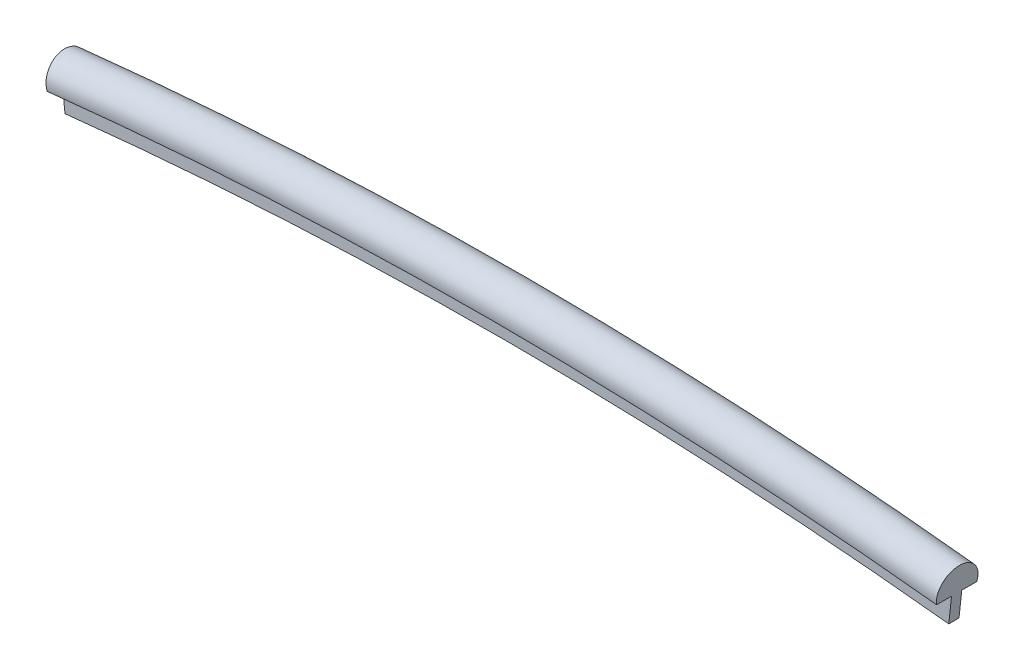
SolidWorks part; units mm, degrees
ref_plane "Front Plane" through (0, 0, 0) normal (0, 0, 1) x (1, 0, 0)
ref_plane "Top Plane" through (0, 0, 0) normal (0, 1, 0) x (1, 0, 0)
ref_plane "Right Plane" through (0, 0, 0) normal (1, 0, 0) x (0, 0, -1)
sketch "Sketch2" plane through (0, 0, 0) normal (1, 0, 0) x (0, 0, -1)
  line L0 (0, 241.3) -> (0, 0) construction
  line L2 (0, 241.3) -> (0, 239.8) construction
  line L3 (0, 239.8) -> (0.3, 239.8)
  line L4 (0, 239.8) -> (-0.3, 239.8)
  line L5 (-0.3, 239.8) -> (-0.3, 241.3)
  line L6 (0.3, 239.8) -> (0.3, 241.3)
  line L7 (0, 241.3) -> (0, 242.8) construction
  line L8 (-1.18, 241.3) -> (-0.3, 241.3)
  line L9 (0.3, 241.3) -> (1.18, 241.3)
  arc A0 (-1.18, 241.3) -> (1.18, 241.3) centre (0, 241.586) cw
  point P14 (0, 241.3)
ref_axis "Axis2" through (0, 0, 70.5976) along (0, 0, -1)
revolve "Revolve1" add sketch "Sketch2" angle 6.202 about axis through (0, 0, 70.5976) along (0, 0, -1)
